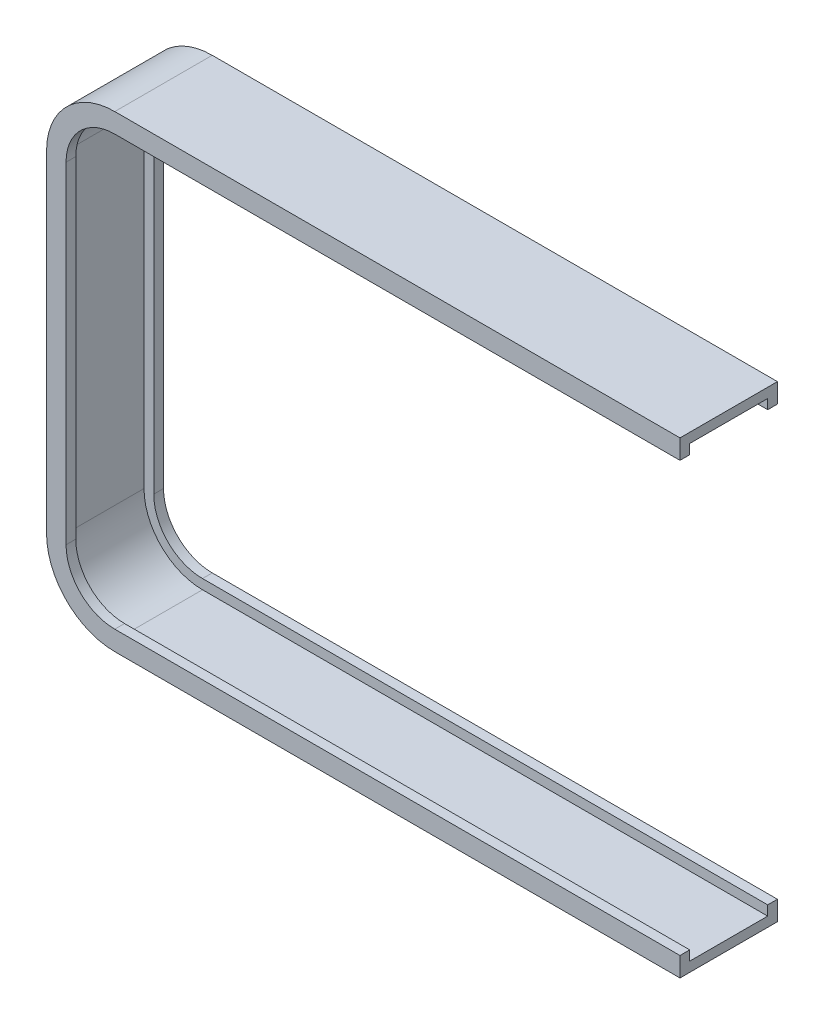
SolidWorks part; units mm, degrees
ref_plane "Alzado" through (0, 0, 0) normal (0, 0, 1) x (1, 0, 0)
ref_plane "Planta" through (0, 0, 0) normal (0, 1, 0) x (1, 0, 0)
ref_plane "Vista lateral" through (0, 0, 0) normal (1, 0, 0) x (0, 0, -1)
sketch "Croquis1" plane through (0, 0, 0) normal (0, 0, 1) x (1, 0, 0)
  line L2 (-2.5, -85) -> (-2.5, 85)
  line L4 (2.5, -85) -> (2.5, 85)
  line L7 (32.5, 120) -> (32.5, 115)
  line L8 (32.5, -120) -> (32.5, -115)
  arc A0 (32.5, 115) -> (2.5, 85) centre (32.5, 85) ccw
  arc A1 (32.5, 120) -> (-2.5, 85) centre (32.5, 85) ccw
  arc A2 (2.5, -85) -> (32.5, -115) centre (32.5, -85) ccw
  arc A4 (-2.5, -85) -> (32.5, -120) centre (32.5, -85) ccw
  point P0 (0, 0)
extrude "Saliente-Extruir1" add sketch "Croquis1" along normal blind 40
sketch "Croquis2" plane through (0, 0, 40) normal (0, 0, 1) x (1, 0, 0)
  line L6 (-2.5, 85) -> (-2.5, -85)
  line L8 (7.5, 85) -> (7.5, -85)
  line L9 (32.5, 120) -> (32.5, 110)
  line L10 (32.5, -120) -> (32.5, -110)
  arc A0 (32.5, 120) -> (-2.5, 85) centre (32.5, 85) ccw
  arc A1 (32.5, 110) -> (7.5, 85) centre (32.5, 85) ccw
  arc A2 (7.5, -85) -> (32.5, -110) centre (32.5, -85) ccw
  arc A3 (-2.5, -85) -> (32.5, -120) centre (32.5, -85) ccw
  point P0 (0, 0)
extrude "Saliente-Extruir2" add sketch "Croquis2" along normal blind 5
ref_plane "Plano1" through (0, 0, 20) normal (0, 0, 1) x (1, 0, 0)
mirror "Simetría1" about plane through (0, 0, 20) normal (0, 0, 1) of "Saliente-Extruir2"
sketch "Croquis3" plane through (32.5, 0, 0) normal (1, 0, 0) x (0, 0, -1)
  line L0 (-45, 120) -> (-45, 110)
  line L1 (-45, 110) -> (-45, 85) construction
  line L2 (-45, 110) -> (-40, 110) construction
  line L3 (-45, 110) -> (-40, 110)
  line L4 (-40, 110) -> (-40, 115)
  line L5 (-40, 115) -> (0, 115)
  line L6 (0, 115) -> (0, 110)
  line L7 (0, 110) -> (5, 110)
  line L8 (5, 85) -> (5, 110) construction
  line L9 (5, 110) -> (0, 110) construction
  line L10 (5, 110) -> (5, 120)
  line L11 (5, 120) -> (-45, 120)
  line L12 (-45, -110) -> (-40, -110)
  line L13 (-40, -110) -> (-40, -115)
  line L14 (-40, -115) -> (0, -115)
  line L15 (0, -115) -> (0, -110)
  line L16 (0, -85) -> (0, -115) construction
  line L17 (0, -110) -> (5, -110)
  line L18 (5, -110) -> (5, -120)
  line L19 (5, -120) -> (5, -85) construction
  line L20 (-45, -120) -> (5, -120) construction
  line L21 (5, -120) -> (-45, -120)
  line L22 (-45, -120) -> (-45, -110) construction
  line L23 (-45, -120) -> (-45, -110)
extrude "Saliente-Extruir3" add sketch "Croquis3" along normal blind 290
